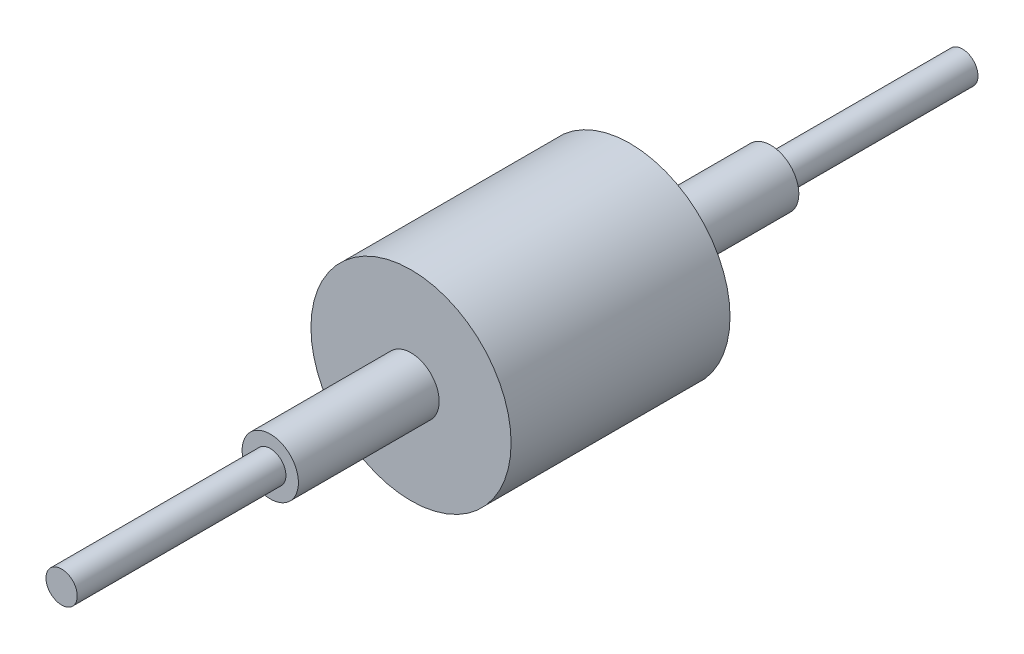
SolidWorks part; units mm, degrees
ref_plane "Front Plane" through (0, 0, 0) normal (0, 0, 1) x (1, 0, 0)
ref_plane "Top Plane" through (0, 0, 0) normal (0, 1, 0) x (1, 0, 0)
ref_plane "Right Plane" through (0, 0, 0) normal (1, 0, 0) x (0, 0, -1)
sketch "Sketch1" plane through (0, 0, 0) normal (0, 1, 0) x (1, 0, 0)
  line L4 (12.7, -23.4242) -> (12.7, 4.357)
  line L5 (0, 0) -> (12.7, 4.357) construction
  line L6 (0, 0) -> (12.7, -23.4242) construction
  line L7 (1.9844, 22.2164) -> (3.5719, 22.2164)
  line L9 (3.5719, 22.2164) -> (3.5719, 4.357)
  line L10 (0, 18.3833) -> (3.5719, 4.357) construction
  line L11 (0, 18.3833) -> (3.5719, 22.2164) construction
  line L13 (1.9844, -41.2836) -> (3.5719, -41.2836)
  line L15 (3.5719, -41.2836) -> (3.5719, -23.4242)
  line L16 (0, -18.3832) -> (3.5719, -23.4242) construction
  line L17 (0, -18.3832) -> (3.5719, -41.2836) construction
  line L18 (3.5719, 4.357) -> (12.7, 4.357)
  line L19 (3.5719, -23.4242) -> (12.7, -23.4242)
  line L20 (0, -1000) -> (0, 49000) construction
  line L21 (0, 22.2164) -> (0, -41.2836)
  line L22 (1.9844, 46.5379) -> (1.9844, 22.2164)
  line L23 (1.9844, 46.5379) -> (0, 46.5379)
  line L26 (1.9844, 46.5379) -> (0, 33.1073) construction
  line L27 (1.9844, 22.2164) -> (0, 33.1073) construction
  line L28 (0, 46.5379) -> (0, 22.2164)
  line L31 (0, -41.2836) -> (0, -67.7621)
  line L32 (0, -67.7621) -> (1.9844, -67.7621)
  line L33 (1.9844, -41.2836) -> (1.9844, -67.7621)
  point P0 (0, 0)
  point P6 (0, 18.3833)
  point P8 (0, -18.3832)
  point P14 (0, 33.1073)
  dimension "D1" = 3.5719
  dimension "D2" = 27.7812
  dimension "D3" = 63.5
  dimension "D4" = 12.7
  dimension "D5" = 1.9844
  dimension "D6" = 114.3
revolve "Revolve2" add sketch "Sketch1" angle 360 about L20
